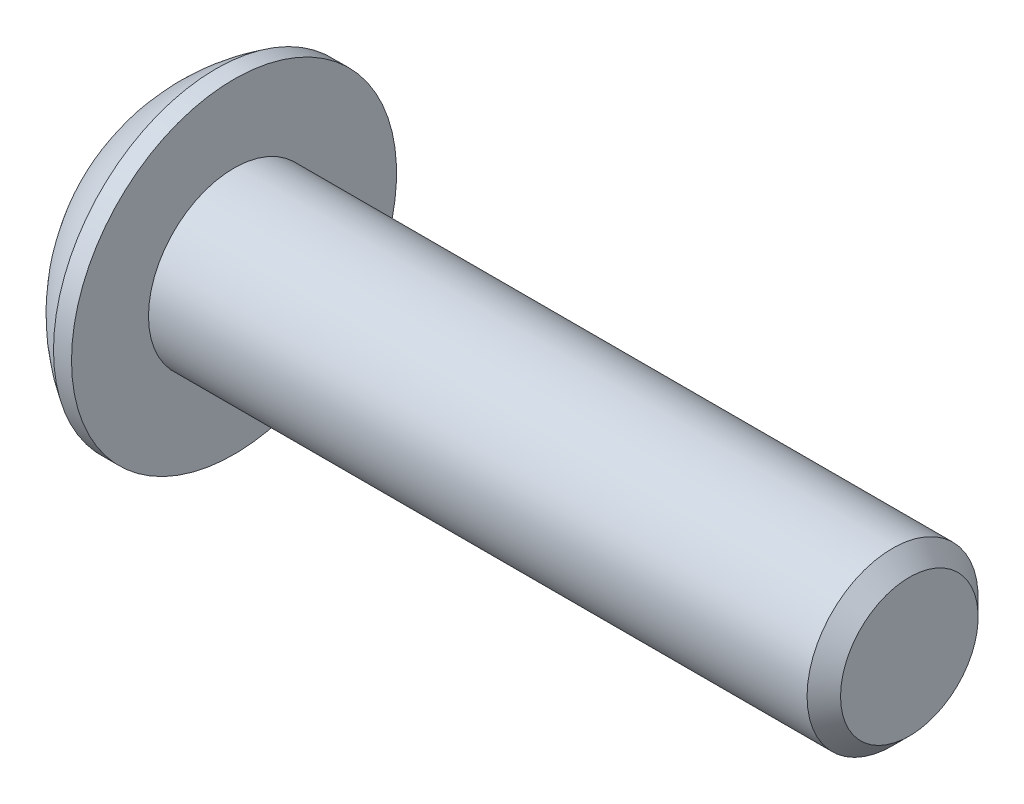
SolidWorks part; units mm, degrees
ref_plane "Plane1" through (0, 0, 0) normal (0, 0, 1) x (1, 0, 0)
ref_plane "Plane2" through (0, 0, 0) normal (0, 1, 0) x (1, 0, 0)
ref_plane "Plane3" through (0, 0, 0) normal (1, 0, 0) x (0, 0, -1)
sketch "BodySke" plane through (0, 0, 0) normal (0, 0, 1) x (1, 0, 0)
  line L0 (21.6154, 0) -> (21.6154, 1.9406)
  line L1 (21.143, 2.413) -> (2.5654, 2.413)
  line L2 (2.5654, 2.413) -> (2.5654, 4.5847)
  line L3 (2.5654, 4.5847) -> (2.0574, 4.5847)
  line L4 (0, 0) -> (101.6, 0) construction
  line L5 (2.5654, -4.5847) -> (2.0574, -4.5847) construction
  line L6 (55.6768, -2.413) -> (2.5654, -2.413) construction
  line L7 (21.6154, 0) -> (0, 0)
  line L8 (0, 2.2923) -> (0, -2.2923) construction
  line L9 (0, 0) -> (0, 2.2923)
  line L10 (21.6154, 1.9406) -> (21.143, 2.413)
  line L11 (21.6154, -1.9406) -> (21.143, -2.413) construction
  line L12 (3.3579, 9.525) -> (3.3579, -2.413) construction
  line L13 (2.5654, 9.525) -> (2.5654, -2.413) construction
  arc A1 (0, 2.2923) -> (2.0574, 4.5847) centre (4.8599, 0) cw
  dimension "Diameter" = 4.826
  dimension "Length" = 19.05
  dimension "Head_dia" = 9.1694
  dimension "D1" = 4.5847
  dimension "Head_ht" = 2.5654
  dimension "Head_side_ht" = 0.508
  dimension "Minor_dia" = 3.8811
  dimension "Body_ch_ang" = 45
  dimension "Advance" = 0.7925
  dimension "Thread_nom" = 19.05
revolve "BaseBody" add sketch "BodySke" angle 360 about L4
cosmetic thread "ThreadCosmetic" [suppressed] parameters "Thread_length"=18.2575, "Thread_minor"=3.8811
sketch "Sketch2" plane through (0, 0, 0) normal (0, 0, 1) x (1, 0, 0)
  line L0 (0, 1.5875) -> (1.778, 1.5875)
  line L1 (1.778, 1.5875) -> (2.6945, 0)
  line L3 (2.6945, 0) -> (0, 0)
  line L4 (0, 0) -> (0, 1.5875)
  line L5 (0, -1.5875) -> (1.778, -1.5875) construction
  line L6 (0, 0) -> (47.625, 0) construction
  dimension "D2" = 60
  dimension "PreBroach_depth" = 1.778
  dimension "PreBroach_dia" = 3.175
revolve "PreBroach" cut sketch "Sketch2" angle 360 about L6
sketch "Sketch3" plane through (0, 0, 0) normal (1, 0, 0) x (0, 0, -1)
  line L0 (-1.5875, -0.9165) -> (-1.5875, 0.9165)
  line L1 (-1.5875, 0.9165) -> (0, 1.8331)
  line L2 (0, 1.8331) -> (1.5875, 0.9165)
  line L3 (1.5875, 0.9165) -> (1.5875, -0.9165)
  line L4 (1.5875, -0.9165) -> (0, -1.8331)
  line L5 (0, -1.8331) -> (-1.5875, -0.9165)
  dimension "Hex_size" = 3.175
  dimension "D3" = 3.175
  dimension "D1" = 1.5875
  dimension "D2" = 1.5875
extrude "Hex" cut sketch "Sketch3" along normal blind 1.778
sketch "Sketch4" plane through (0, 9.525, 0) normal (1, 0, 0) x (0, 0, -1)
  line L0 (0, -9.525) -> (1.8923, -9.525)
  line L1 (0, -9.525) -> (6.1484, -5.9752) construction
  line L2 (0, -9.525) -> (0.9461, -7.8862)
  line L3 (1.5663, -9.09) -> (1.8037, -8.9529)
  line L4 (1.1599, -8.3861) -> (1.3973, -8.249)
  arc A0 (1.5663, -9.09) -> (1.1599, -8.3861) centre (0, -9.525) ccw
  arc A1 (1.8923, -9.525) -> (1.8037, -8.9529) centre (0, -9.525) ccw
  arc A2 (0.9461, -7.8862) -> (1.3973, -8.249) centre (0, -9.525) cw
  dimension "Spline_n_dim" = 3.2512
  dimension "Spline_m_dim" = 3.7846
  dimension "D1" = 30
  dimension "D2" = 60
  dimension "Spline_p_dim" = 0.8128
  dimension "D3" = 0.4064
extrude "Spline" [suppressed] cut sketch "Sketch4" along normal blind 1.778
pattern_circular "CirPattern1" [suppressed] count 6 every 60 about axis through (0, 0, 0) along (1, 0, 0)
sketch "ThdSchSke" plane through (0, 0, 0) normal (0, 0, 1) x (1, 0, 0)
  line L0 (3.3579, -1.9406) -> (3.0271, -2.413)
  line L1 (3.3579, -1.9406) -> (3.6887, -2.413)
  line L2 (3.6887, -2.413) -> (3.6887, -3.0163)
  line L3 (-3.175, 0) -> (5.1513, 0) construction
  line L5 (3.6887, -3.0163) -> (3.0271, -3.0163)
  line L6 (3.0271, -3.0163) -> (3.0271, -2.413)
  dimension "Diameter" = 4.826
  dimension "Thread_minor" = 3.8811
  dimension "SideAngle" = 55
  dimension "VeeAngle" = 70
  dimension "Overcut" = 6.0325
  dimension "Start" = 3.3579
revolve "ThreadSchematic" [suppressed] cut sketch "ThdSchSke" angle 360 about L3
pattern_linear "ThdSchPat" [suppressed]
equation "\"D1@BodySke\" = \"Head_dia@BodySke\" * .5"
equation "\"Thread_minor@ThreadCosmetic\" = \"Minor_dia@BodySke\""
equation "\"D1@Sketch3\" = \"Hex_size@Sketch3\" / 2"
equation "\"D2@Sketch3\" = \"D1@Sketch3\""
equation "\"D3@Sketch3\" = \"Hex_size@Sketch3\""
equation "\"D3@Sketch4\" = \"Spline_p_dim@Sketch4\" / 2"
equation "\"D1@Sketch4\" = \"D2@Sketch4\" / 2"
equation "\"Thread_length@ThreadCosmetic\" = ((sgn( (\"Length@BodySke\" - \"Advance@BodySke\" ) - \"Thread_nom@BodySke\" )-1)*( (\"Length@BodySke\" - \"Advance@BodySke\" ) - \"Thread_nom@BodySke\" ))/-2+ \"Thread_nom@BodySke\""
equation "\"Thread_minor@ThdSchSke\" = \"Minor_dia@BodySke\""
equation "\"Diameter@ThdSchSke\" = \"Diameter@BodySke\""
equation "\"Overcut@ThdSchSke\" = \"Diameter@BodySke\" * 1.25"
equation "\"Start@ThdSchSke\" = \"Head_ht@BodySke\" + \"Length@BodySke\" - \"Thread_length@ThreadCosmetic\"  '---Non-countersunk---"
equation "\"Num_threads@ThdSchPat\" = int( \"Thread_length@ThreadCosmetic\" / \"Advance@BodySke\" + 0.999 )  + 1"
equation "\"Advance@ThdSchPat\" = \"Thread_length@ThreadCosmetic\" /  (\"Num_threads@ThdSchPat\" - 1) 'relax it"
equation "\"Num_threads@ThdSchPat\" = \"Num_threads@ThdSchPat\" - sgn( \"Num_threads@ThdSchPat\" - 1) '---chamfered tips only---"
